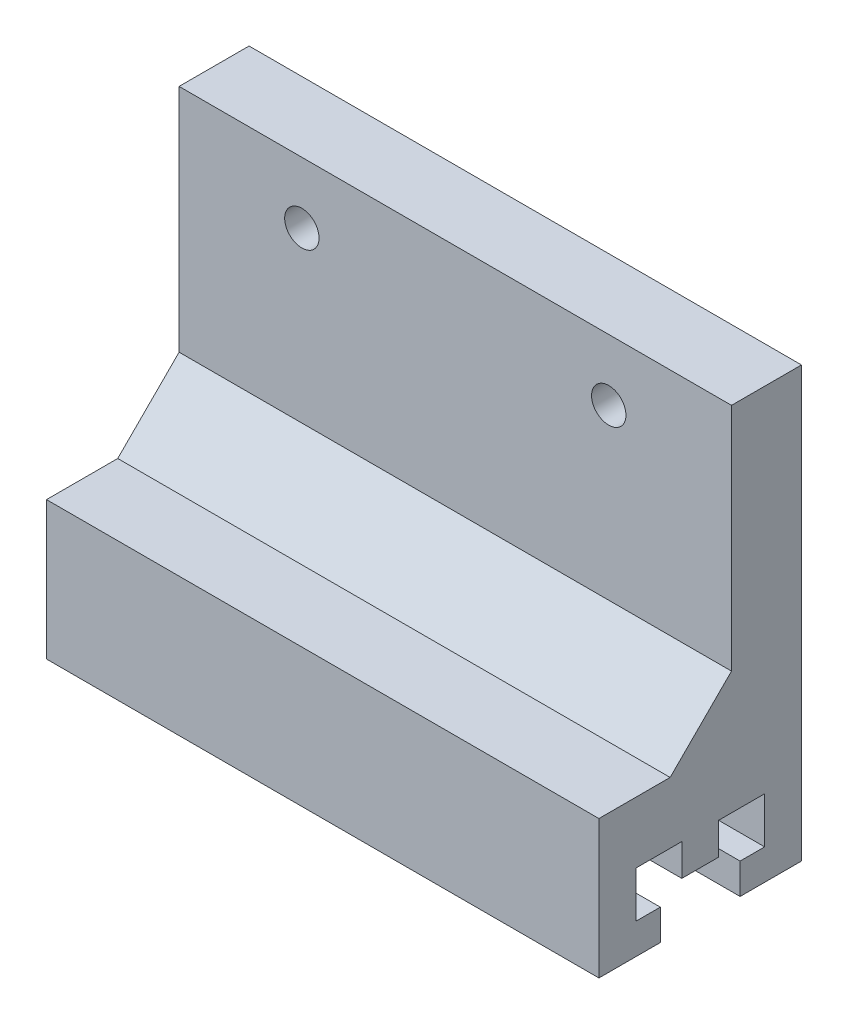
SolidWorks part; units mm, degrees
ref_plane "Front Plane" through (0, 0, 0) normal (0, 0, 1) x (1, 0, 0)
ref_plane "Top Plane" through (0, 0, 0) normal (0, 1, 0) x (1, 0, 0)
ref_plane "Right Plane" through (0, 0, 0) normal (1, 0, 0) x (0, 0, -1)
sketch "Sketch1" plane through (0, 0, 0) normal (1, 0, 0) x (0, 0, -1)
  line L3 (-16.5, 7.5) -> (16.5, 7.5)
  line L5 (-10.5, -2.5) -> (-10.5, -10)
  line L6 (-10.5, -2.5) -> (-3, -2.5)
  line L8 (-3, -2.5) -> (-3, -7.7)
  line L9 (-3, -7.7) -> (3, -7.7)
  line L10 (3, -2.5) -> (3, -7.7)
  line L15 (-10.5, -10) -> (-6.5, -10)
  line L18 (-6.5, -10) -> (-6.5, -15)
  line L23 (6.5, -10) -> (10.5, -10)
  line L24 (6.5, -10) -> (6.5, -15)
  line L26 (3, -2.5) -> (10.5, -2.5)
  line L27 (10.5, -2.5) -> (10.5, -10)
  line L29 (-16.5, -15) -> (-6.5, -15)
  line L30 (6.5, -15) -> (16.5, -15)
  line L31 (-16.5, 7.5) -> (-16.5, -15)
  line L32 (16.5, 7.5) -> (16.5, -15)
  point P0 (0, 0)
  point P22 (0, -7.7)
  point P25 (0, 7.5)
  dimension "D1" = 33
  dimension "D3" = 6
  dimension "D4" = 0
  dimension "D5" = 0
  dimension "D6" = 7.5
  dimension "D7" = 7.5
  dimension "D8" = 7.5
  dimension "D9" = 7.5
  dimension "D10" = 4
  dimension "D11" = 5
  dimension "D12" = 4
  dimension "D13" = 5
  dimension "D14" = 10
  dimension "D15" = 10
  dimension "D17" = 2.5
  dimension "D18" = 7.7
  dimension "D19" = 2.5
extrude "Boss-Extrude1" add sketch "Sketch1" along normal blind 90 contours L29 L18 L15 L5 L6 L8 L9 L10 L26 L27 L23 L24 L30 L32 L3 L31
sketch "Sketch3" plane through (0, 7.5, 0) normal (0, 1, 0) x (1, 0, 0)
  line L6 (0, 16.5) -> (90, 16.5)
  line L7 (90, 16.5) -> (90, 5.1)
  line L8 (90, -16.5) -> (90, 16.5) construction
  line L9 (90, 5.1) -> (0, 5.1)
  line L10 (0, -16.5) -> (0, 16.5) construction
  line L11 (0, 5.1) -> (0, 16.5)
  dimension "D1" = 11.4
extrude "Boss-Extrude3" add sketch "Sketch3" along normal blind 47.5
sketch "Sketch6" plane through (0, 0, -16.5) normal (0, 0, -1) x (-1, 0, 0)
  line L0 (0, 55) -> (0, -15) construction
  line L1 (-90, 55) -> (-90, -15) construction
  line L2 (-90, 55) -> (0, 55) construction
  circle A0 centre (-70, 45) radius 5.5
  circle A1 centre (-20, 45) radius 5.5
  dimension "D4" = 11
  dimension "D6" = 11
  dimension "D1" = 20
  dimension "D2" = 20
  dimension "D3" = 10
  dimension "D5" = 10
extrude "Cut-Extrude3" cut sketch "Sketch6" against normal blind 5.5
sketch "Sketch7" plane through (0, 0, -11) normal (0, 0, -1) x (-1, 0, 0)
  circle A0 centre (-70, 45) radius 2.8
  circle A1 centre (-20, 45) radius 2.8
  dimension "D1" = 5.6
  dimension "D2" = 5.6
extrude "Cut-Extrude4" cut sketch "Sketch7" against normal blind 10
sketch "Sketch11" plane through (0, 0, 0) normal (-1, 0, 0) x (0, 0, 1)
  line L0 (-5.1, 17.5) -> (4.9, 7.5)
  line L1 (-5.1, 55) -> (-5.1, 7.5) construction
  line L2 (16.5, 7.5) -> (-5.1, 7.5) construction
  line L3 (4.9, 7.5) -> (-5.1, 7.5)
  line L4 (-5.1, 7.5) -> (-5.1, 17.5)
  dimension "D1" = 10
  dimension "D2" = 10
extrude "Boss-Extrude4" add sketch "Sketch11" against normal blind 90
